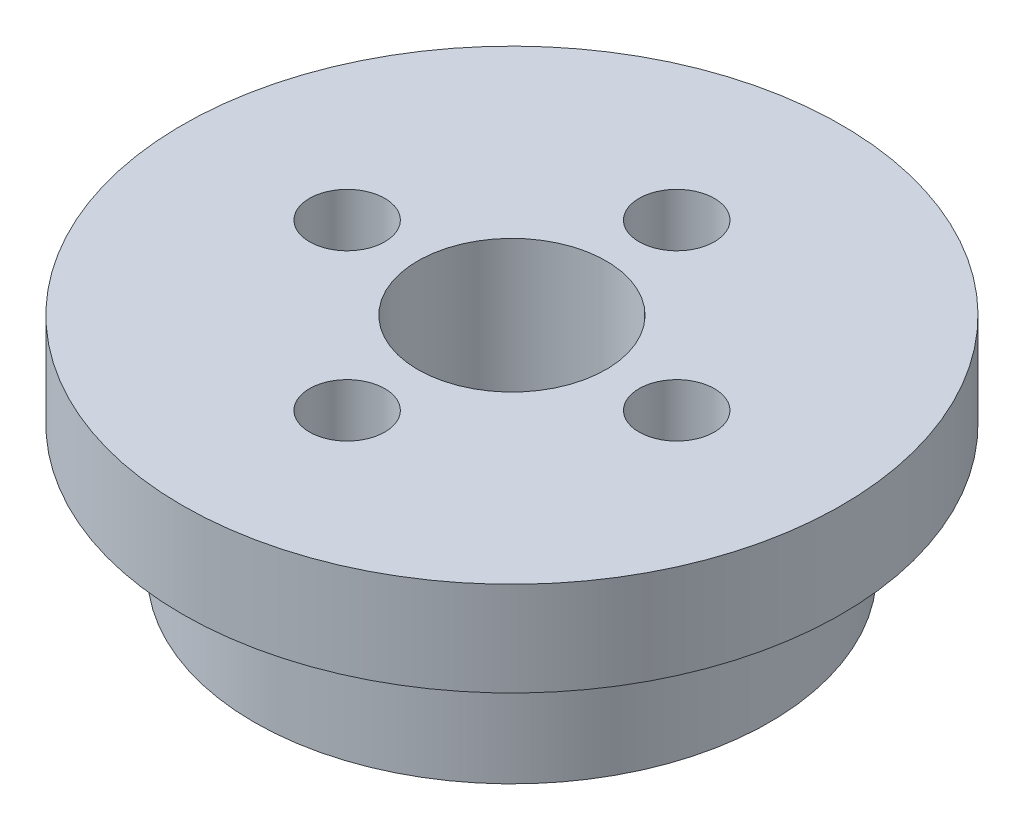
SolidWorks part; units mm, degrees
ref_plane "前视基准面" through (0, 0, 0) normal (0, 0, 1) x (1, 0, 0)
ref_plane "上视基准面" through (0, 0, 0) normal (0, 1, 0) x (1, 0, 0)
ref_plane "右视基准面" through (0, 0, 0) normal (1, 0, 0) x (0, 0, -1)
sketch "草图3" plane through (0, 0, 0) normal (0, 1, 0) x (1, 0, 0)
  circle A0 centre (0, 0) radius 10.95
  dimension "D1" = 21.9
extrude "凸台-拉伸1" add sketch "草图3" along normal blind 5.5
sketch "草图4" plane through (0, 5.5, 0) normal (0, 1, 0) x (1, 0, 0)
  circle A0 centre (0, 0) radius 14
  dimension "D1" = 28
extrude "凸台-拉伸2" add sketch "草图4" along normal blind 4
sketch "草图5" plane through (0, 9.5, 0) normal (0, 1, 0) x (1, 0, 0)
  line L0 (0, -14) -> (0, 14) construction
  line L1 (-4.65, 1.3568) -> (-7, 2.7135) construction
  line L2 (-1.3568, -4.65) -> (-2.7135, -7) construction
  line L3 (-2.7135, -7) -> (-1.3568, -9.35) construction
  line L4 (-1.3568, -9.35) -> (1.3568, -9.35) construction
  line L5 (1.3568, -9.35) -> (2.7135, -7) construction
  line L6 (2.7135, -7) -> (1.3568, -4.65) construction
  line L7 (1.3568, -4.65) -> (-1.3568, -4.65) construction
  line L8 (-7, 2.7135) -> (-9.35, 1.3568) construction
  line L9 (-9.35, 1.3568) -> (-9.35, -1.3568) construction
  line L10 (-9.35, -1.3568) -> (-7, -2.7135) construction
  line L11 (-7, -2.7135) -> (-4.65, -1.3568) construction
  line L12 (-4.65, -1.3568) -> (-4.65, 1.3568) construction
  line L13 (-14, 0) -> (14, 0) construction
  line L14 (1.3568, 4.65) -> (2.7135, 7) construction
  line L15 (2.7135, 7) -> (1.3568, 9.35) construction
  line L16 (1.3568, 9.35) -> (-1.3568, 9.35) construction
  line L17 (-1.3568, 9.35) -> (-2.7135, 7) construction
  line L18 (-2.7135, 7) -> (-1.3568, 4.65) construction
  line L19 (-1.3568, 4.65) -> (1.3568, 4.65) construction
  line L20 (0, 14) -> (0, -14) construction
  line L21 (4.65, -1.3568) -> (7, -2.7135) construction
  line L22 (7, -2.7135) -> (9.35, -1.3568) construction
  line L23 (9.35, -1.3568) -> (9.35, 1.3568) construction
  line L24 (9.35, 1.3568) -> (7, 2.7135) construction
  line L25 (7, 2.7135) -> (4.65, 1.3568) construction
  line L26 (4.65, 1.3568) -> (4.65, -1.3568) construction
  line L27 (14, 0) -> (-14, 0) construction
  circle A0 centre (0, 0) radius 4
  circle A1 centre (-7, 0) radius 2.35 construction
  circle A2 centre (0, 0) radius 14 construction
  circle A3 centre (0, -7) radius 2.35 construction
  circle A4 centre (0, 7) radius 2.35 construction
  circle A6 centre (7, 0) radius 2.35 construction
  circle A7 centre (0, 7) radius 1.6
  circle A8 centre (7, 0) radius 1.6
  circle A9 centre (0, -7) radius 1.6
  circle A10 centre (-7, 0) radius 1.6
  point P37 (0.1299, -0.075)
  point P43 (0, 0)
  point P45 (0, 0)
  point P51 (0, 0)
  point P56 (0, 0)
  dimension "D1" = 4
  dimension "D3" = 8
  dimension "D2" = 4.7
  dimension "D4" = 3.2
  dimension "D5" = 4
extrude "切除-拉伸1" cut sketch "草图5" against normal blind 50
